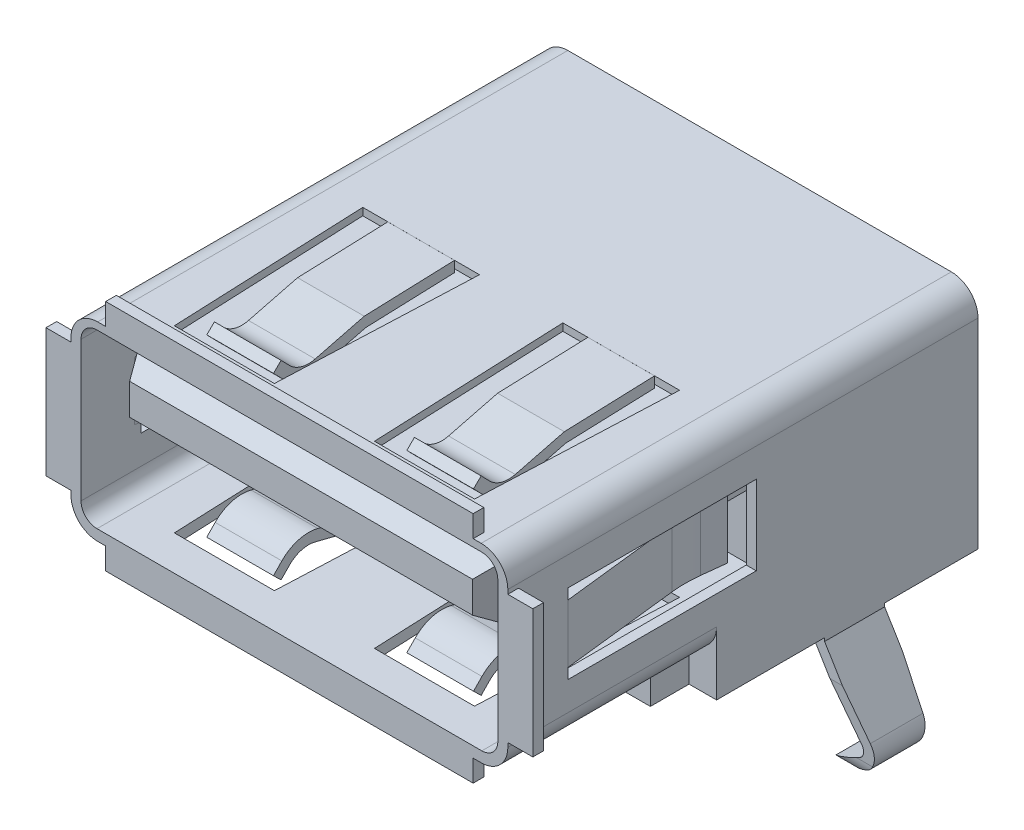
SolidWorks part; units mm, degrees
ref_plane "Front" through (0, 0, 0) normal (0, 0, 1) x (1, 0, 0)
ref_plane "Top" through (0, 0, 0) normal (0, 1, 0) x (1, 0, 0)
ref_plane "Side" through (0, 0, 0) normal (1, 0, 0) x (0, 0, -1)
ref_plane "Position 1 Plane" through (-3.5, 0, 0) normal (1, 0, 0) x (0, 0, -1)
sketch "Sketch1" plane through (0, 0, 0) normal (0, 1, 0) x (1, 0, 0)
  line L0 (6.55, -7.05) -> (-6.55, 7.05) construction
  line L1 (-6.55, 7.05) -> (6.55, 7.05)
  line L2 (-6.55, 7.05) -> (-6.55, -7.05)
  line L3 (-6.55, -7.05) -> (6.55, -7.05)
  line L4 (6.55, 7.05) -> (6.55, -7.05)
  dimension "D1" = 13.1
  dimension "D2" = 14.1
extrude "Base" add sketch "Sketch1" along normal blind 5.7
ref_plane "Ground Tail Plane" through (0, 0, -3.35) normal (0, 0, 1) x (1, 0, 0)
ref_plane "Top/Bottom Flange Plane" through (-3, 0, 0) normal (1, 0, 0) x (0, 0, -1)
ref_plane "Mid Plane" through (0, 2.85, 0) normal (0, 1, 0) x (-1, 0, 0)
ref_plane "Back Plane" through (0, 0, -7.05) normal (0, 0, 1) x (1, 0, 0)
ref_plane "Cut Plane" through (0, 0, -1.85) normal (0, 0, 1) x (1, 0, 0)
sketch "Sketch3" plane through (0, 0, 7.05) normal (0, 0, 1) x (1, 0, 0)
  line L0 (-6.55, 5.7) -> (6.55, 5.7) construction
  line L1 (-5.51, 5.7) -> (5.51, 5.7)
  line L2 (-5.51, 5.7) -> (-5.51, 6.35)
  line L3 (-5.51, 6.35) -> (5.51, 6.35)
  line L4 (5.51, 5.7) -> (5.51, 6.35)
  line L5 (6.55, 5.7) -> (6.55, 0) construction
  line L6 (6.55, 4.775) -> (7.3, 4.775)
  line L7 (6.55, 4.775) -> (6.55, 0.925)
  line L8 (6.55, 0.925) -> (7.3, 0.925)
  line L9 (7.3, 4.775) -> (7.3, 0.925)
  line L10 (0, 6.35) -> (0, 5.7) construction
  line L11 (6.55, 2.85) -> (7.3, 2.85) construction
  line L12 (-6.55, 5.7) -> (6.55, 0) construction
  line L13 (0, 2.85) -> (3.5942, 2.85) construction
  line L14 (5.51, 0) -> (5.51, -0.65)
  line L15 (-5.51, -0.65) -> (5.51, -0.65)
  line L16 (-5.51, 0) -> (-5.51, -0.65)
  line L17 (-5.51, 0) -> (5.51, 0)
  line L18 (0, 2.85) -> (0, 4.7958) construction
  line L19 (-7.3, 4.775) -> (-7.3, 0.925)
  line L20 (-6.55, 0.925) -> (-7.3, 0.925)
  line L21 (-6.55, 4.775) -> (-6.55, 0.925)
  line L22 (-6.55, 4.775) -> (-7.3, 4.775)
  dimension "D1" = 14.6
  dimension "D2" = 11.02
  dimension "D3" = 7
  dimension "D4" = 3.85
extrude "Front Tabs" add sketch "Sketch3" against normal blind 0.32
fillet "Corner Fillets" radius 0.8 4 edges at (-6.55, 5.7, 0) (-6.55, 0, 0) (6.55, 0, 0) (6.55, 5.7, 0)
sketch "Sketch18" plane through (0, 0, -7.05) normal (0, 0, -1) x (-1, 0, 0)
  line L0 (-6.55, 0.8) -> (-6.55, -1.1)
  line L1 (-6.55, -1.1) -> (6.55, -1.1)
  line L2 (6.55, -1.1) -> (6.55, 0.8)
  line L3 (-5.75, 0) -> (5.75, 0) construction
  line L4 (-5.75, 0) -> (5.75, 0)
  line L5 (0, 0) -> (0, -1.6279) construction
  arc A2 (-6.55, 0.8) -> (-5.75, 0) centre (-5.75, 0.8) ccw
  arc A3 (5.75, 0) -> (6.55, 0.8) centre (5.75, 0.8) ccw
  point P13 (0, -1.1)
  dimension "D2" = 0.8
  dimension "D1" = 1.1
extrude "-D Back Step" add sketch "Sketch18" against normal blind 7.84
sketch "Sketch19" plane through (0, 0, 0) normal (0, -1, 0) x (1, 0, 0)
  line L0 (6.55, 0.79) -> (-6.55, 0.79) construction
  line L1 (5.725, 0.79) -> (-5.725, 0.79)
  line L2 (5.725, 0.79) -> (5.725, 1.95)
  line L3 (5.725, 1.95) -> (-5.725, 1.95)
  line L4 (-5.725, 0.79) -> (-5.725, 1.95)
  line L5 (0, 1.95) -> (0, 0.79) construction
  line L6 (6.55, -7.05) -> (-6.55, -7.05) construction
  dimension "D1" = 9
  dimension "D2" = 11.45
extrude "-D Bottom Step" add sketch "Sketch19" along normal up to surface (1.1 mm away) up to face at (0, -1.1, -3.13)
sketch "Sketch22" plane through (0, 0, -7.05) normal (0, 0, -1) x (-1, 0, 0)
  line L4 (-6.55, 0.8) -> (-6.55, -1.1)
  line L5 (-6.55, -1.1) -> (6.55, -1.1)
  line L6 (6.55, -1.1) -> (6.55, 0.8)
  line L7 (5.75, 0) -> (-5.75, 0)
  line L8 (-6.55, 0.8) -> (-6.55, -1.1)
  line L9 (-6.55, -1.1) -> (6.55, -1.1)
  line L10 (6.55, -1.1) -> (6.55, 0.8)
  line L11 (5.75, 0) -> (-5.75, 0)
  arc A2 (5.75, 0) -> (6.55, 0.8) centre (5.75, 0.8) ccw
  arc A3 (-6.55, 0.8) -> (-5.75, 0) centre (-5.75, 0.8) ccw
  arc A4 (5.75, 0) -> (6.55, 0.8) centre (5.75, 0.8) ccw
  arc A5 (-6.55, 0.8) -> (-5.75, 0) centre (-5.75, 0.8) ccw
  dimension "D1" = 0
extrude "-S Back Step" add sketch "Sketch22" against normal blind 5.2
sketch "Sketch21" plane through (0, 0, 0) normal (0, -1, 0) x (1, 0, 0)
  line L1 (-1.2, -1.85) -> (1.2, -1.85)
  line L2 (5.75, -7.05) -> (-5.75, -7.05) construction
  line L5 (-1.2, 1.35) -> (1.2, 1.35)
  line L6 (-1.2, 1.35) -> (-1.2, -1.85)
  line L7 (1.2, 1.35) -> (1.2, -1.85)
  line L9 (0, 0) -> (0, -9.4203) construction
  point P10 (0, 1.35)
  dimension "D1" = 2.4
  dimension "D2" = 5.2
  dimension "D3" = 3.2
extrude "-S Bottom Step" add sketch "Sketch21" along normal blind 1.1
sketch "Sketch10" plane through (0, 0, -3.35) normal (0, 0, 1) x (1, 0, 0)
  line L0 (6.55, -1.2) -> (6.55, -1.1)
  line L2 (6.55, -1.2) -> (7.8102, -3.2786)
  line L3 (7.5651, -4.1506) -> (6.6971, -4.6)
  line L4 (7.5365, -3.4445) -> (6.23, -1.2894)
  line L5 (-5.75, 0) -> (-5.51, 0) construction
  line L6 (5.725, 0) -> (-5.725, 0) construction
  line L7 (6.55, 0.925) -> (6.55, 0.8) construction
  line L8 (6.23, -1.1) -> (6.23, -1.2894)
  line L9 (7.4179, -3.8664) -> (6.55, -4.3158)
  line L10 (6.55, -4.3158) -> (6.6971, -4.6)
  line L11 (6.23, -1.1) -> (6.23, -1.2071) construction
  line L12 (6.55, -1.1) -> (6.23, -1.1)
  line L13 (0, 0) -> (0, -2.9377) construction
  line L14 (6.3579, -1.5004) -> (7.5365, -3.4445) construction
  line L15 (-6.55, -1.1) -> (-6.23, -1.1)
  line L16 (-6.55, -4.3158) -> (-6.6971, -4.6)
  line L17 (-7.4179, -3.8664) -> (-6.55, -4.3158)
  line L18 (-6.23, -1.1) -> (-6.23, -1.2894)
  line L19 (-6.23, -1.2894) -> (-7.5365, -3.4445)
  line L20 (-7.5651, -4.1506) -> (-6.6971, -4.6)
  line L21 (-6.55, -1.2) -> (-7.8102, -3.2786)
  line L22 (-6.55, -1.2) -> (-6.55, -1.1)
  line L24 (6.3579, -1.5004) -> (6.3579, -1.5004) construction
  line L25 (6.3579, -1.5004) -> (6.3579, -1.5004) construction
  line L26 (6.3579, -1.5004) -> (6.3579, -1.5004) construction
  arc A0 (7.8102, -3.2786) -> (7.5651, -4.1506) centre (7.28, -3.6) cw
  arc A1 (7.5365, -3.4445) -> (7.4179, -3.8664) centre (7.28, -3.6) cw
  arc A2 (-7.5365, -3.4445) -> (-7.4179, -3.8664) centre (-7.28, -3.6) ccw
  arc A3 (-7.8102, -3.2786) -> (-7.5651, -4.1506) centre (-7.28, -3.6) ccw
  arc A4 (7.8102, -3.2786) -> (7.5651, -4.1506) centre (7.28, -3.6) cw construction
  dimension "D2" = 0.32
  dimension "D5" = 0.3
  dimension "D7" = 15.8
  dimension "D6" = 3.6
  dimension "D1" = 13.1
  dimension "D3" = 4.6
  dimension "D4" = 0.1
  dimension "D8" = 0.32
  dimension "D9" = 1.1
extrude "Ground Tail 1" add sketch "Sketch10" along normal mid plane 1.8
sketch "Sketch11" plane through (0, 0, 0) normal (1, 0, 0) x (0, 0, -1)
  line L0 (2.425, -1.8091) -> (2.6183, -3.9065)
  line L1 (3.35, 7.92) -> (3.35, -7.92) construction
  line L3 (4.275, -1.8091) -> (4.0817, -3.9065)
  line L4 (2.425, -1.8091) -> (2.425, -4.9391)
  line L6 (2.425, -4.9391) -> (4.275, -4.9391)
  line L7 (4.275, -4.9391) -> (4.275, -1.8091)
  line L8 (3.35, -4.85) -> (3.35, -6.7183) construction
  arc A0 (2.6183, -3.9065) -> (4.0817, -3.9065) centre (3.35, -3.8391) ccw
  point P5 (3.35, -4.9391)
  dimension "D2" = 0.7348
  dimension "D1" = 1.85
  dimension "D3" = 1.1
  dimension "D4" = 4.9391
  dimension "D5" = 2.0974
extrude "Ground Tail 1 Shape" cut sketch "Sketch11" against normal mid plane 16
sketch "Sketch23" plane through (0, 0, 0) normal (0, -1, 0) x (1, 0, 0)
  line L0 (-3.5098, -5.9128) -> (-3.5098, -6.2228) construction
  line L1 (-3.1796, -5.9128) -> (-3.84, -5.9128)
  line L2 (-3.1796, -5.9128) -> (-3.1796, -6.2228)
  line L3 (-3.1796, -6.2228) -> (-3.84, -6.2228)
  line L4 (-3.84, -5.9128) -> (-3.84, -6.2228)
  line L5 (-3.1796, -6.0678) -> (-3.84, -6.0678) construction
  line L6 (3.16, -5.9128) -> (3.16, -6.2228)
  line L7 (3.8204, -5.9128) -> (3.16, -5.9128)
  line L8 (3.8204, -5.9128) -> (3.8204, -6.2228)
  line L9 (3.8204, -6.2228) -> (3.16, -6.2228)
  line L10 (-1.34, -5.9128) -> (-1.34, -6.2228)
  line L11 (-0.6796, -5.9128) -> (-1.34, -5.9128)
  line L12 (-0.6796, -5.9128) -> (-0.6796, -6.2228)
  line L13 (-0.6796, -6.2228) -> (-1.34, -6.2228)
  line L14 (0.66, -5.9128) -> (0.66, -6.2228)
  line L15 (1.3204, -5.9128) -> (0.66, -5.9128)
  line L16 (1.3204, -5.9128) -> (1.3204, -6.2228)
  line L17 (1.3204, -6.2228) -> (0.66, -6.2228)
  line L18 (0, 0) -> (0, -8.093) construction
  line L19 (7.92, -3.35) -> (-7.92, -3.35) construction
  dimension "D1" = 2.5
  dimension "D2" = 2
  dimension "D3" = 2.5
  dimension "D4" = 0.31
  dimension "D5" = 1.34
  dimension "D6" = 0.6604
  dimension "D7" = 2.7178
extrude "-TH Contact Tail" add sketch "Sketch23" along normal blind 3.9
sketch "Sketch8" plane through (0, 0, 7.05) normal (0, 0, 1) x (1, 0, 0)
  line L0 (-6.25, 5) -> (-6.25, 0.8)
  line L1 (-5.77, 0.32) -> (5.77, 0.32)
  line L2 (-5.77, 5.48) -> (5.77, 5.48)
  line L3 (6.25, 0.8) -> (6.25, 5)
  line L4 (0, 0) -> (0, 6.7662) construction
  arc A16 (6.25, 5) -> (5.77, 5.48) centre (5.77, 5) ccw
  arc A17 (5.77, 0.32) -> (6.25, 0.8) centre (5.77, 0.8) ccw
  arc A18 (-6.25, 0.8) -> (-5.77, 0.32) centre (-5.77, 0.8) ccw
  arc A19 (-5.77, 5.48) -> (-6.25, 5) centre (-5.77, 5) ccw
  point P4 (0, 5.48)
  dimension "D2" = 0.48
  dimension "D1" = 12.5
  dimension "D3" = 0.32
  dimension "D4" = 5.16
extrude "Contact Area Cutout" cut sketch "Sketch8" against normal blind 8.85
sketch "Sketch12" plane through (0, 0, 0) normal (0, 1, 0) x (-1, 0, 0)
  line L0 (0, 0) -> (0, 5.7946) construction
  line L1 (4.5, 6) -> (4.75, 0.1)
  line L2 (3, 4.5748) -> (3, 0.3752) construction
  line L3 (1.5, 6) -> (1.25, 0.1)
  line L4 (4.5, 6) -> (1.5, 6)
  line L5 (4.75, 0.1) -> (1.25, 0.1)
  line L7 (-4.75, 0.1) -> (-1.25, 0.1)
  line L8 (-4.5, 6) -> (-1.5, 6)
  line L9 (-1.5, 6) -> (-1.25, 0.1)
  line L10 (-4.5, 6) -> (-4.75, 0.1)
  dimension "D1" = 3.5
  dimension "D2" = 3
  dimension "D3" = 5.9
  dimension "D4" = 6
  dimension "D5" = 3
extrude "Top/Bottom Flange Cutout" cut sketch "Sketch12" along normal blind 5.8
sketch "Sketch13" plane through (-3, 0, 0) normal (1, 0, 0) x (0, 0, -1)
  line L0 (-2.7601, 0.4175) -> (-4.1983, 0.7842)
  line L1 (7.05, 2.85) -> (-8.6639, 2.85) construction
  line L2 (-2.8059, 5.6011) -> (-4.2773, 5.2259)
  line L3 (-5.0476, 5.4424) -> (-5.3, 5.7011)
  line L4 (-5.2766, 5.2189) -> (-5.529, 5.4776)
  line L5 (-2.7601, 5.2825) -> (-4.1983, 4.9158)
  line L6 (-2.8059, 5.6011) -> (-0.1, 5.699)
  line L7 (-5.529, 5.4776) -> (-5.3, 5.7011)
  line L8 (-0.1, 5.699) -> (-0.1, 5.3788)
  line L9 (-0.79, 0) -> (-7.05, 0) construction
  line L10 (-5.3, 5.7011) -> (-5.3, -0.0011) construction
  line L12 (-2.7601, 0.4175) -> (-0.1, 0.3212)
  line L13 (-0.1, 0.001) -> (-0.1, 0.3212)
  line L14 (-5.529, 0.2224) -> (-5.3, -0.0011)
  line L15 (-2.8059, 0.0989) -> (-0.1, 0.001)
  line L16 (-5.2766, 0.4811) -> (-5.529, 0.2224)
  line L17 (-2.7601, 5.2825) -> (-0.1, 5.3788)
  line L18 (-5.0476, 0.2576) -> (-5.3, -0.0011)
  line L19 (-2.8059, 0.0989) -> (-4.2773, 0.4741)
  line L20 (0.6313, 2.85) -> (-0.6313, 2.85) construction
  arc A0 (-4.2773, 5.2259) -> (-5.0476, 5.4424) centre (-4.475, 6.0011) cw
  arc A1 (-4.1983, 4.9158) -> (-5.2766, 5.2189) centre (-4.475, 6.0011) cw
  arc A2 (-4.1983, 0.7842) -> (-5.2766, 0.4811) centre (-4.475, -0.3011) ccw
  arc A3 (-4.2773, 0.4741) -> (-5.0476, 0.2576) centre (-4.475, -0.3011) ccw
  point P15 (-5.3, 2.85)
  dimension "D3" = 0.8
  dimension "D6" = 5.2
  dimension "D8" = 0.4
  dimension "D2" = 4.375
  dimension "D4" = 2.7059
  dimension "D5" = 0.32
  dimension "D7" = 0.3614
  dimension "D9" = 0.32
  dimension "D10" = 5.7021
  dimension "D11" = 0.1
  dimension "D13" = 0.001
extrude "Top/Bottom Flange" add sketch "Sketch13" along normal mid plane 2
pattern_linear "Top/Bottom Flange Pattern" count 2 spacing 6 along (1, 0, 0) of "Top/Bottom Flange"
sketch "Sketch14" plane through (6.55, 0, 0) normal (1, 0, 0) x (0, 0, -1)
  line L0 (0.6313, 2.85) -> (-0.6313, 2.85) construction
  line L1 (-5.25, 4.04) -> (0.4, 4.04)
  line L2 (-5.25, 4.04) -> (-5.25, 1.66)
  line L3 (-5.25, 1.66) -> (0.4, 1.66)
  line L4 (0.4, 4.04) -> (0.4, 1.66)
  line L7 (7.05, 2.85) -> (-7.9068, 2.85) construction
  line L8 (-7.05, 0.925) -> (-7.05, 0.8) construction
  point P4 (-5.25, 2.85)
  dimension "D1" = 2.38
  dimension "D2" = 5.65
  dimension "D3" = 1.8
extrude "Side Flange Cutout" cut sketch "Sketch14" against normal through all
sketch "Sketch15" plane through (0, 2.85, 0) normal (0, 1, 0) x (-1, 0, 0)
  line L0 (6.55, 5.25) -> (6.149, 1.7237)
  line L1 (6.1488, 0.8778) -> (6.2313, 0.15)
  line L2 (6.55, 5.25) -> (6.25, 5.25) construction
  line L3 (6.55, 7.05) -> (6.55, -7.05) construction
  line L4 (5.8309, 0.8418) -> (5.9133, 0.114)
  line L5 (6.25, 5.444) -> (5.8311, 1.7598)
  line L6 (6.25, 5.444) -> (6.55, 5.25)
  line L7 (5.9133, 0.114) -> (6.2313, 0.15)
  line L8 (0, 0) -> (0, 6.0458) construction
  line L9 (-5.9133, 0.114) -> (-6.2313, 0.15)
  line L10 (-6.25, 5.444) -> (-6.55, 5.25)
  line L11 (-6.25, 5.444) -> (-5.8311, 1.7598)
  line L12 (-5.8309, 0.8418) -> (-5.9133, 0.114)
  line L13 (-6.1488, 0.8778) -> (-6.2313, 0.15)
  line L14 (-6.55, 5.25) -> (-6.149, 1.7237)
  line L15 (6.25, -1.8) -> (6.25, 7.05) construction
  arc A0 (6.149, 1.7237) -> (6.1488, 0.8778) centre (9.875, 1.3) ccw
  arc A1 (5.8311, 1.7598) -> (5.8309, 0.8418) centre (9.875, 1.3) ccw
  arc A2 (-5.8311, 1.7598) -> (-5.8309, 0.8418) centre (-9.875, 1.3) cw
  arc A3 (-6.149, 1.7237) -> (-6.1488, 0.8778) centre (-9.875, 1.3) cw
  dimension "D2" = 3.75
  dimension "D3" = 3.95
  dimension "D4" = 3.325
  dimension "D6" = 3.6437
  dimension "D1" = 5.1
  dimension "D5" = 0.32
extrude "Side Flange" add sketch "Sketch15" along normal mid plane 1.75
sketch "Sketch16" plane through (0, 0, -1.8) normal (0, 0, 1) x (1, 0, 0)
  line L0 (0, 4.72) -> (0, 2.92) construction
  line L1 (-5.575, 4.72) -> (5.575, 4.72)
  line L2 (-5.575, 4.72) -> (-5.575, 2.92)
  line L3 (-5.575, 2.92) -> (5.575, 2.92)
  line L4 (5.575, 4.72) -> (5.575, 2.92)
  line L6 (5.77, 5.48) -> (-5.77, 5.48) construction
  dimension "D1" = 2.56
  dimension "D3" = 1.8
  dimension "D4" = 11.15
extrude "Contact Guide" add sketch "Sketch16" along normal blind 8.5
chamfer "Contact Guide Lead-in" distance 0.75 angle 30 4 edges at (0, 2.92, 6.7) (-5.575, 3.82, 6.7) (0, 4.72, 6.7) (5.575, 3.82, 6.7)
sketch "Sketch17" plane through (-3.5, 0, 0) normal (1, 0, 0) x (0, 0, -1)
  line L0 (1.8, 3.91) -> (1.8, 3.65)
  line L1 (1.8, 4.72) -> (1.8, 2.92) construction
  line L2 (1.8, 3.65) -> (0.55, 3.65)
  line L3 (0.55, 3.65) -> (-3.0129, 2.5075)
  line L4 (-4.9162, 2.7571) -> (-5.45, 3.1)
  line L9 (1.8, 0.8) -> (1.8, 5) construction
  line L10 (-4.7757, 2.9758) -> (-5.3095, 3.3187)
  line L11 (0.5093, 3.91) -> (-3.0923, 2.755)
  line L12 (1.8, 3.91) -> (0.5093, 3.91)
  line L13 (-5.95, 2.92) -> (1.8, 2.92) construction
  line L15 (-5.45, 3.1) -> (-5.3095, 3.3187)
  arc A0 (-3.0129, 2.5075) -> (-4.9162, 2.7571) centre (-3.7, 4.65) cw
  arc A1 (-3.0923, 2.755) -> (-4.7757, 2.9758) centre (-3.7, 4.65) cw
  dimension "D5" = 2.25
  dimension "D6" = 1
  dimension "D7" = 4.25
  dimension "D2" = 0.73
  dimension "D4" = 1.25
  dimension "D8" = 0.55
  dimension "D9" = 6
  dimension "D10" = 0.26
extrude "Contact" add sketch "Sketch17" along normal mid plane 0.66
pattern_linear "Contact Pattern" count 2 spacing 2.5 along (1, 0, 0) of "Contact"
mirror "Contact Pattern Mirror" about plane through (0, 0, 0) normal (1, 0, 0) of "Contact", "Contact Pattern"
sketch "Sketch24" plane through (0, 0, -1.85) normal (0, 0, 1) x (1, 0, 0)
  line L0 (0, 0) -> (0, 7.67) construction
  line L1 (7.5, 7) -> (-7.5, 7)
  line L2 (7.5, 7) -> (7.5, -5)
  line L3 (7.5, -5) -> (-7.5, -5)
  line L4 (-7.5, 7) -> (-7.5, -5)
  point P7 (0, 7)
  dimension "D1" = 15
  dimension "D2" = 5
  dimension "D3" = 12
